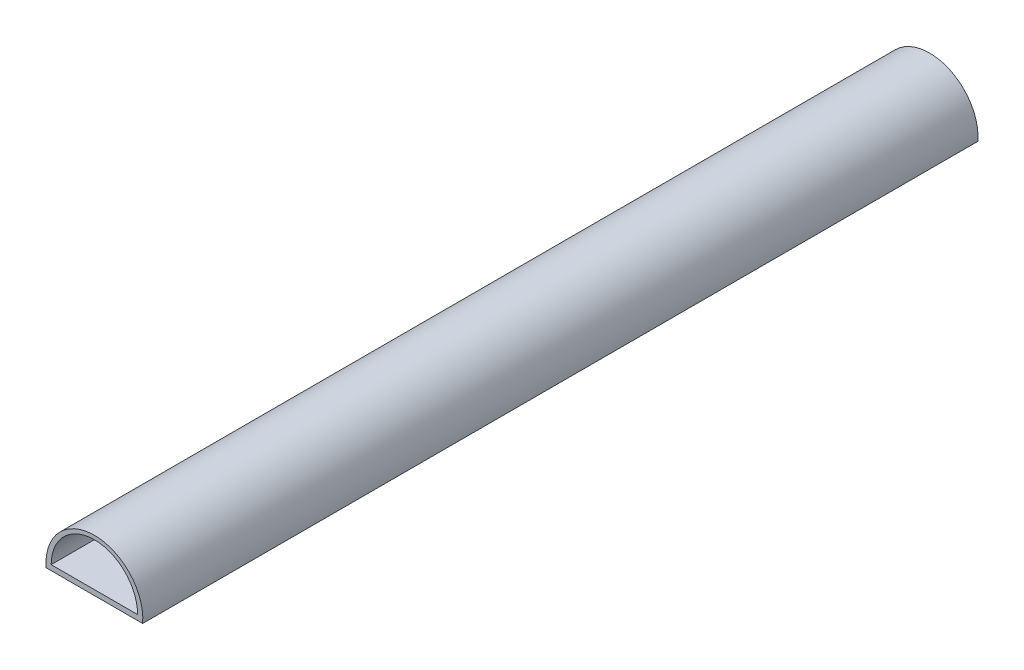
SolidWorks part; units mm, degrees
material "PVC 0.007 Plasticized"
ref_plane "Front Plane" through (0, 0, 0) normal (0, 0, 1) x (1, 0, 0)
ref_plane "Top Plane" through (0, 0, 0) normal (0, 1, 0) x (1, 0, 0)
ref_plane "Right Plane" through (0, 0, 0) normal (1, 0, 0) x (0, 0, -1)
sketch "Sketch1" plane through (0, 0, 0) normal (0, 0, 1) x (1, 0, 0)
  line L0 (-23.1114, -10.0484) -> (6.2574, -10.0484)
  line L2 (-8.427, -8.4609) -> (-21.5715, -8.4609)
  line L3 (-8.427, -8.4609) -> (4.7175, -8.4609)
  arc A0 (-23.1114, -10.0484) -> (6.2574, -10.0484) centre (-8.427, -8.8769) cw
  arc A1 (-21.5715, -8.4609) -> (4.7175, -8.4609) centre (-8.427, -8.4609) cw
extrude "Boss-Extrude2" add sketch "Sketch1" along normal blind 254
